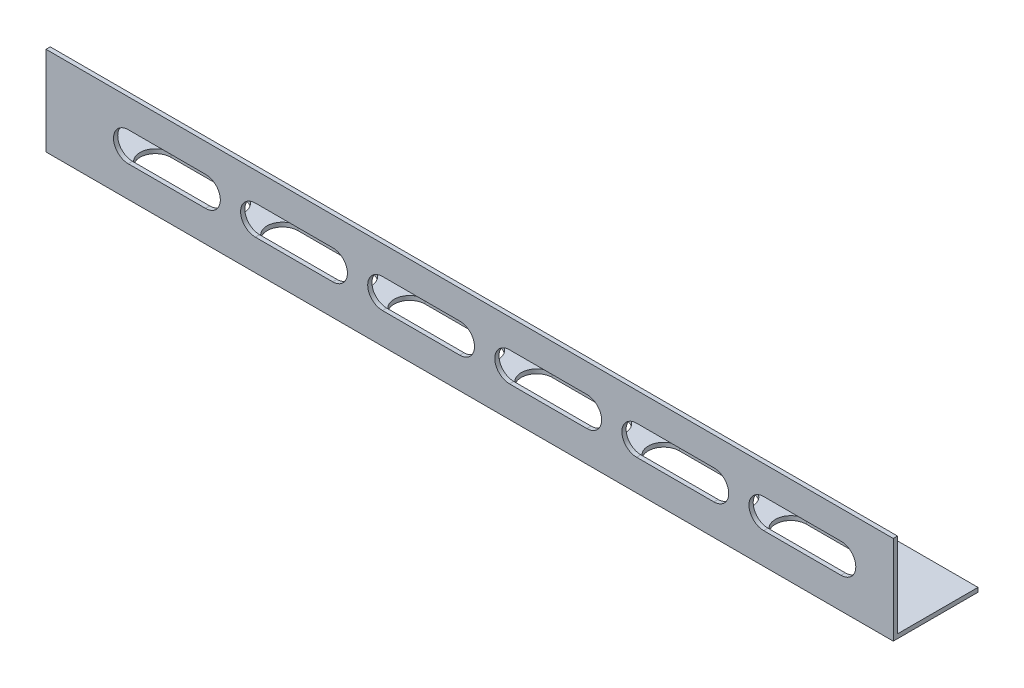
SolidWorks part; units mm, degrees
ref_plane "Front Plane" through (0, 0, 0) normal (0, 0, 1) x (1, 0, 0)
ref_plane "Top Plane" through (0, 0, 0) normal (0, 1, 0) x (1, 0, 0)
ref_plane "Right Plane" through (0, 0, 0) normal (1, 0, 0) x (0, 0, -1)
sketch "Sketch1" plane through (0, 0, 0) normal (0, 1, 0) x (1, 0, 0)
  line L1 (-75, 20) -> (75, 20)
  line L2 (-75, 20) -> (-75, -20)
  line L3 (-75, -20) -> (75, -20)
  line L4 (75, 20) -> (75, -20)
  line L5 (-75, 20) -> (75, -20) construction
  line L6 (-75, -20) -> (75, 20) construction
  point P0 (0, 0)
  dimension "D1" = 150
  dimension "D2" = 40
extrude "Boss-Extrude1" add sketch "Sketch1" along normal blind 2
sketch "Sketch2" plane through (0, 2, 0) normal (0, 1, 0) x (1, 0, 0)
  line L0 (75, -20) -> (75, 20) construction
  line L1 (-75, -20) -> (75, -20)
  line L2 (-75, -20) -> (-75, -18)
  line L3 (-75, -18) -> (75, -18)
  line L4 (75, -20) -> (75, -18)
  dimension "D1" = 2
extrude "Boss-Extrude2" add sketch "Sketch2" along normal blind 40
sketch "Sketch5" plane through (75, 0, 0) normal (1, 0, 0) x (0, 0, -1)
  line L12 (-20, 0) -> (20, 0)
  line L13 (20, 0) -> (20, 2)
  line L14 (20, 2) -> (-18, 2)
  line L15 (-18, 2) -> (-18, 42)
  line L16 (-18, 42) -> (-20, 42)
  line L17 (-20, 42) -> (-20, 0)
  line L18 (-20, 0) -> (20, 0)
  line L19 (20, 0) -> (20, 2)
  line L20 (20, 2) -> (-18, 2)
  line L21 (-18, 2) -> (-18, 42)
  line L22 (-18, 42) -> (-20, 42)
  line L23 (-20, 42) -> (-20, 0)
  dimension "D1" = 0
extrude "Boss-Extrude3" add sketch "Sketch5" along normal blind 250
sketch "Sketch6" plane through (0, 0, 18) normal (0, 0, -1) x (-1, 0, 0)
  line L0 (-240.3374, 28.5374) -> (-203.8332, 28.5374)
  line L1 (-300.3374, 28.5374) -> (-263.8332, 28.5374)
  line L3 (-300.3374, 14.6081) -> (-263.8332, 14.6081)
  line L5 (-300.3374, 28.5374) -> (-263.8332, 14.6081) construction
  line L6 (-300.3374, 14.6081) -> (-263.8332, 28.5374) construction
  line L7 (-240.3374, 14.6081) -> (-203.8332, 14.6081)
  line L8 (-180.3374, 28.5374) -> (-143.8332, 28.5374)
  line L9 (-180.3374, 14.6081) -> (-143.8332, 14.6081)
  line L10 (-120.3374, 28.5374) -> (-83.8332, 28.5374)
  line L11 (-120.3374, 14.6081) -> (-83.8332, 14.6081)
  line L12 (-60.3374, 28.5374) -> (-23.8332, 28.5374)
  line L13 (-60.3374, 14.6081) -> (-23.8332, 14.6081)
  line L14 (-0.3374, 28.5374) -> (36.1668, 28.5374)
  line L15 (-0.3374, 14.6081) -> (36.1668, 14.6081)
  arc A0 (-263.8332, 28.5374) -> (-263.8332, 14.6081) centre (-263.8332, 21.5728) cw
  arc A1 (-300.3374, 28.5374) -> (-300.3374, 14.6081) centre (-300.3374, 21.5728) ccw
  arc A2 (-203.8332, 28.5374) -> (-203.8332, 14.6081) centre (-203.8332, 21.5728) cw
  arc A3 (-240.3374, 28.5374) -> (-240.3374, 14.6081) centre (-240.3374, 21.5728) ccw
  arc A4 (-143.8332, 28.5374) -> (-143.8332, 14.6081) centre (-143.8332, 21.5728) cw
  arc A5 (-180.3374, 28.5374) -> (-180.3374, 14.6081) centre (-180.3374, 21.5728) ccw
  arc A6 (-83.8332, 28.5374) -> (-83.8332, 14.6081) centre (-83.8332, 21.5728) cw
  arc A7 (-120.3374, 28.5374) -> (-120.3374, 14.6081) centre (-120.3374, 21.5728) ccw
  arc A8 (-23.8332, 28.5374) -> (-23.8332, 14.6081) centre (-23.8332, 21.5728) cw
  arc A9 (-60.3374, 28.5374) -> (-60.3374, 14.6081) centre (-60.3374, 21.5728) ccw
  arc A10 (36.1668, 28.5374) -> (36.1668, 14.6081) centre (36.1668, 21.5728) cw
  arc A11 (-0.3374, 28.5374) -> (-0.3374, 14.6081) centre (-0.3374, 21.5728) ccw
  point P0 (-282.0853, 21.5728)
  dimension "D1" = 6
extrude "Cut-Extrude1" cut sketch "Sketch6" against normal blind 10
sketch "Sketch7" plane through (0, 0, 0) normal (0, -1, 0) x (1, 0, 0)
  line L0 (16.6756, 7.302) -> (51.1908, 7.302)
  line L1 (-43.3244, 7.302) -> (-8.8092, 7.302)
  line L3 (-43.3244, -7.302) -> (-8.8092, -7.302)
  line L5 (-43.3244, 7.302) -> (-8.8092, -7.302) construction
  line L6 (-43.3244, -7.302) -> (-8.8092, 7.302) construction
  line L7 (16.6756, -7.302) -> (51.1908, -7.302)
  line L8 (76.6756, 7.302) -> (111.1908, 7.302)
  line L9 (76.6756, -7.302) -> (111.1908, -7.302)
  line L10 (136.6756, 7.302) -> (171.1908, 7.302)
  line L11 (136.6756, -7.302) -> (171.1908, -7.302)
  line L12 (196.6756, 7.302) -> (231.1908, 7.302)
  line L13 (196.6756, -7.302) -> (231.1908, -7.302)
  line L14 (256.6756, 7.302) -> (291.1908, 7.302)
  line L15 (256.6756, -7.302) -> (291.1908, -7.302)
  arc A0 (-8.8092, 7.302) -> (-8.8092, -7.302) centre (-8.8092, 0) cw
  arc A1 (-43.3244, 7.302) -> (-43.3244, -7.302) centre (-43.3244, 0) ccw
  arc A2 (51.1908, 7.302) -> (51.1908, -7.302) centre (51.1908, 0) cw
  arc A3 (16.6756, 7.302) -> (16.6756, -7.302) centre (16.6756, 0) ccw
  arc A4 (111.1908, 7.302) -> (111.1908, -7.302) centre (111.1908, 0) cw
  arc A5 (76.6756, 7.302) -> (76.6756, -7.302) centre (76.6756, 0) ccw
  arc A6 (171.1908, 7.302) -> (171.1908, -7.302) centre (171.1908, 0) cw
  arc A7 (136.6756, 7.302) -> (136.6756, -7.302) centre (136.6756, 0) ccw
  arc A8 (231.1908, 7.302) -> (231.1908, -7.302) centre (231.1908, 0) cw
  arc A9 (196.6756, 7.302) -> (196.6756, -7.302) centre (196.6756, 0) ccw
  arc A10 (291.1908, 7.302) -> (291.1908, -7.302) centre (291.1908, 0) cw
  arc A11 (256.6756, 7.302) -> (256.6756, -7.302) centre (256.6756, 0) ccw
  point P0 (-26.0668, 0)
  dimension "D1" = 6
extrude "Cut-Extrude2" cut sketch "Sketch7" against normal blind 10
